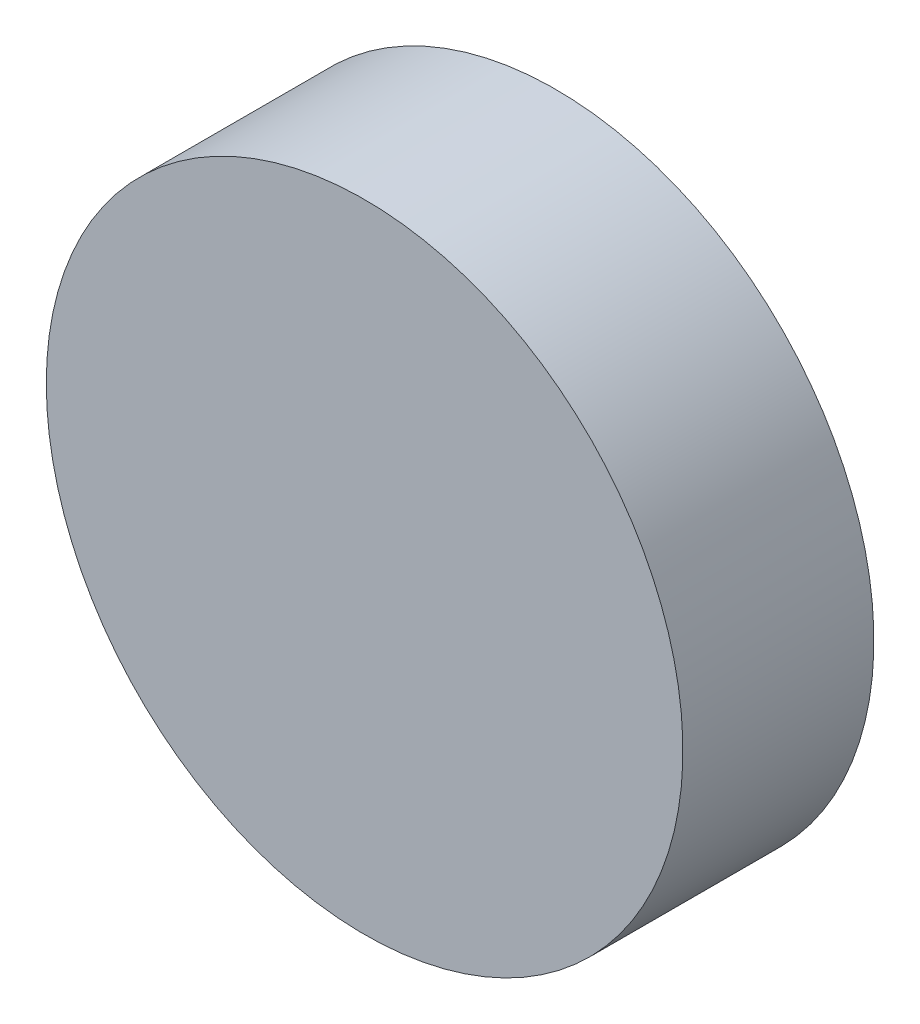
SolidWorks part; units mm, degrees
ref_plane "Přední rovina" through (0, 0, 0) normal (0, 0, 1) x (1, 0, 0)
ref_plane "Horní rovina" through (0, 0, 0) normal (0, 1, 0) x (1, 0, 0)
ref_plane "Pravá rovina" through (0, 0, 0) normal (1, 0, 0) x (0, 0, -1)
sketch "Sketch1" plane through (0, 0, 0) normal (0, 1, 0) x (1, 0, 0)
  line L1 (-25, 0) -> (-15, 0)
  line L2 (-25, 0) -> (-25, -15)
  line L3 (-25, -15) -> (0, -15)
  line L6 (-15, 0) -> (-15, -10)
  line L7 (-15, -10) -> (0, -10)
  line L9 (0, 0) -> (0, -15) construction
  line L13 (0, -15) -> (0, -10)
  point P3 (0, -10)
  dimension "D1" = 25
  dimension "D2" = 10
  dimension "D3" = 10
  dimension "D4" = 5
revolve "Revolve1" add sketch "Sketch1" angle 360 about L9
